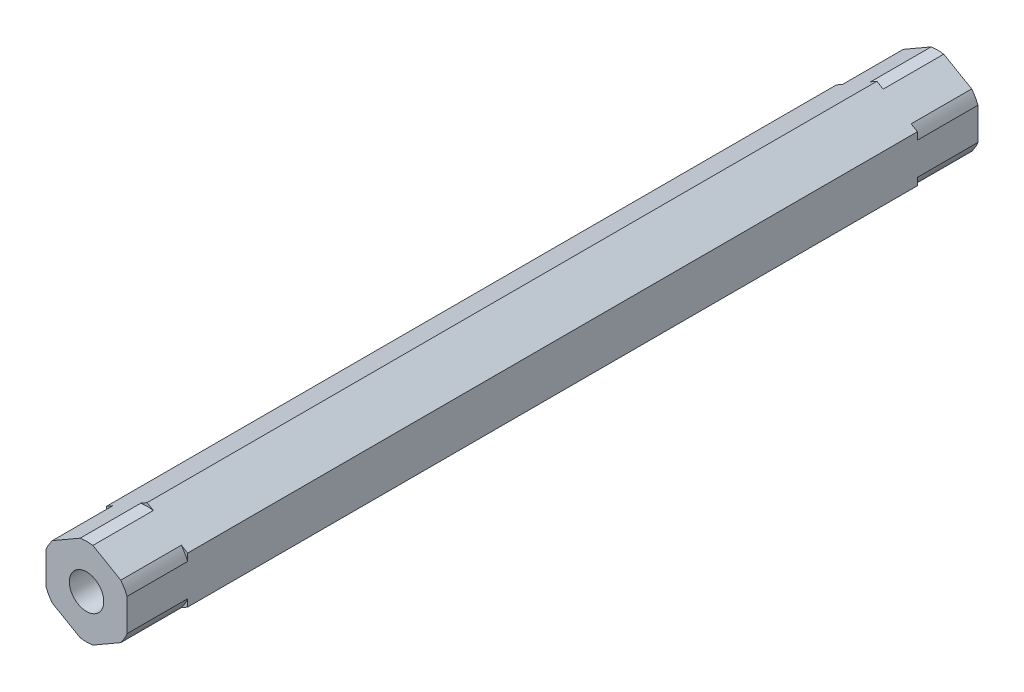
SolidWorks part; units mm, degrees
material "7075-T6 (SN)"
ref_plane "Front Plane" through (0, 0, 0) normal (0, 0, 1) x (1, 0, 0)
ref_plane "Top Plane" through (0, 0, 0) normal (0, 1, 0) x (1, 0, 0)
ref_plane "Right Plane" through (0, 0, 0) normal (1, 0, 0) x (0, 0, -1)
sketch "Sketch1" plane through (0, 0, 0) normal (0, 0, 1) x (1, 0, 0)
  line L1 (4.7625, 2.7496) -> (0, 5.4993)
  line L2 (0, 5.4993) -> (-4.7625, 2.7496)
  line L3 (-4.7625, 2.7496) -> (-4.7625, -2.7496)
  line L4 (-4.7625, -2.7496) -> (0, -5.4993)
  line L5 (0, -5.4993) -> (4.7625, -2.7496)
  line L6 (4.7625, -2.7496) -> (4.7625, 2.7496)
  circle A0 centre (0, 0) radius 4.7625 construction
  dimension "D2" = 9.525
extrude "Boss-Extrude1" add sketch "Sketch1" along normal mid plane 99.949
sketch "Sketch2" plane through (0, 0, -49.9745) normal (0, 0, -1) x (-1, 0, 0)
  circle A0 centre (0, 0) radius 2.0193
  dimension "D1" = 4.0386
extrude "Cut-Extrude1" cut sketch "Sketch2" against normal blind 19.05
mirror "Mirror1" about plane through (0, 0, 0) normal (0, 0, 1) of "Cut-Extrude1"
sketch "Sketch3" plane through (0, 0, -49.9745) normal (0, 0, -1) x (-1, 0, 0)
  circle A0 centre (0, 0) radius 5.125
  circle A1 centre (0, 0) radius 11.0648
  dimension "D1" = 10.25
extrude "Cut-Extrude2" cut sketch "Sketch3" against normal blind 7.112
mirror "Mirror2" about plane through (0, 0, 0) normal (0, 0, 1) of "Cut-Extrude2"
